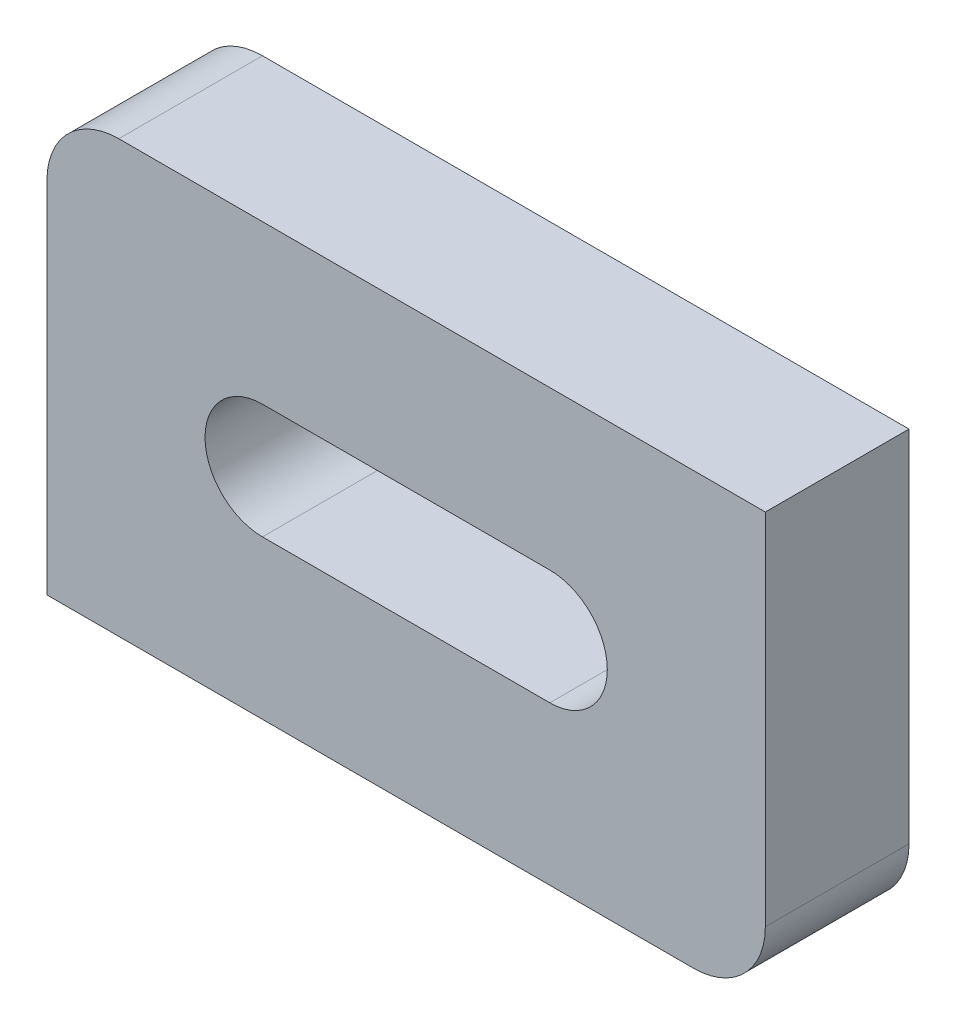
SolidWorks part; units mm, degrees
ref_plane "Front Plane" through (0, 0, 0) normal (0, 0, 1) x (1, 0, 0)
ref_plane "Top Plane" through (0, 0, 0) normal (0, 1, 0) x (1, 0, 0)
ref_plane "Right Plane" through (0, 0, 0) normal (1, 0, 0) x (0, 0, -1)
sketch "Sketch1" plane through (0, 0, 0) normal (0, 0, 1) x (1, 0, 0)
  line L0 (0, 0) -> (45, 0)
  line L1 (50, 5) -> (50, 30)
  line L2 (50, 30) -> (5, 30)
  line L3 (0, 25) -> (0, 0)
  line L4 (15, 15) -> (35, 15) construction
  line L5 (15, 19) -> (35, 19)
  line L6 (15, 11) -> (35, 11)
  arc A0 (50, 5) -> (45, 0) centre (45, 5) cw
  arc A1 (0, 25) -> (5, 30) centre (5, 25) cw
  arc A2 (15, 19) -> (15, 11) centre (15, 15) ccw
  arc A3 (35, 11) -> (35, 19) centre (35, 15) ccw
  point P11 (25, 15)
  point P16 (0, 0)
  dimension "D1" = 5
  dimension "D2" = 5
extrude "Boss-Extrude1" add sketch "Sketch1" along normal blind 10
